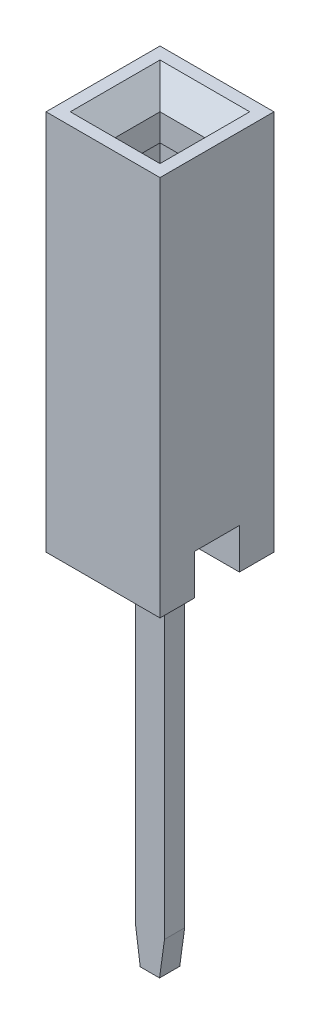
SolidWorks part; units mm, degrees
ref_plane "Vorne" through (0, 0, 0) normal (0, 0, 1) x (1, 0, 0)
ref_plane "Oben" through (0, 0, 0) normal (0, 1, 0) x (1, 0, 0)
ref_plane "Rechts" through (0, 0, 0) normal (1, 0, 0) x (0, 0, -1)
sketch "Sketch1" plane through (0, 0, 0) normal (0, 1, 0) x (1, 0, 0)
  line L1 (1.27, -1.27) -> (-1.27, -1.27)
  line L2 (1.27, -1.27) -> (1.27, 1.27)
  line L3 (1.27, 1.27) -> (-1.27, 1.27)
  line L4 (-1.27, -1.27) -> (-1.27, 1.27)
  line L5 (1.27, -1.27) -> (-1.27, 1.27) construction
  line L6 (1.27, 1.27) -> (-1.27, -1.27) construction
  point P0 (0, 0)
  dimension "D1" = 2.54
extrude "Boss-Extrude1" add sketch "Sketch1" along normal blind 8.5
shell "Shell1" thickness 0.77
chamfer "Chamfer1" distance 0.5 angle 45 4 edges at (-0.5, 8.5, 0) (0, 8.5, 0.5) (0.5, 8.5, 0) (0, 8.5, -0.5)
sketch "Sketch2" plane through (0, 0, 0) normal (1, 0, 0) x (0, 0, -1)
  line L0 (1.27, 0) -> (-1.27, 0) construction
  line L1 (0.5, 0) -> (-0.5, 0)
  line L2 (0.5, 0) -> (0.5, 0.9)
  line L3 (0.5, 0.9) -> (-0.5, 0.9)
  line L4 (-0.5, 0) -> (-0.5, 0.9)
  dimension "D1" = 1
  dimension "D2" = 0.9
extrude "Cut-Extrude1" cut sketch "Sketch2" against normal through all both and the other way through all
sketch "Sketch3" plane through (0, 0, 0) normal (0, 1, 0) x (1, 0, 0)
  line L1 (1, 1) -> (-1, 1)
  line L2 (1, 1) -> (1, -1)
  line L3 (1, -1) -> (-1, -1)
  line L4 (-1, 1) -> (-1, -1)
  line L5 (1, 1) -> (-1, -1) construction
  line L6 (1, -1) -> (-1, 1) construction
  point P0 (0, 0)
  dimension "D1" = 2
extrude "Cut-Extrude3" cut sketch "Sketch3" along normal blind 6 from offset 1.4
sketch "Sketch4" plane through (0, 0, 0) normal (0, 0, 1) x (1, 0, 0)
  line L0 (-1, 7.3) -> (-1, 1.4)
  line L1 (0, 8.5) -> (0, 0) construction
  line L2 (-0.325, -7.2) -> (-0.215, -8)
  line L3 (-0.6, 4.9) -> (-0.6, 2.8)
  line L4 (-0.325, 1.4) -> (-0.325, -7.2)
  line L5 (-0.5, 1.4) -> (0.5, 1.4) construction
  line L6 (-0.325, 1.4) -> (-1, 1.4)
  line L7 (-0.215, -8) -> (0.215, -8)
  line L8 (-1.27, 0) -> (1.27, 0) construction
  line L9 (-0.8375, 7.3296) -> (-0.6, 6.7)
  line L10 (0.8375, 7.3296) -> (0.6, 6.7)
  line L11 (0.325, 1.4) -> (1, 1.4)
  line L12 (0.325, 1.4) -> (0.325, -7.2)
  line L13 (0.6, 4.9) -> (0.6, 2.8)
  line L14 (0.325, -7.2) -> (0.215, -8)
  line L15 (1, 7.3) -> (1, 1.4)
  arc A0 (-0.6, 2.8) -> (0.6, 2.8) centre (0, 2.8) ccw
  arc A1 (-0.6, 4.9) -> (-0.6, 6.7) centre (-2.9859, 5.8) ccw
  arc A2 (-1, 7.3) -> (-0.8375, 7.3296) centre (-0.9161, 7.3) cw
  arc A3 (1, 7.3) -> (0.8375, 7.3296) centre (0.9161, 7.3) ccw
  arc A4 (0.6, 4.9) -> (0.6, 6.7) centre (2.9859, 5.8) cw
  point P29 (0, -8)
  dimension "D10" = 2.55
  dimension "D1" = 1
  dimension "D2" = 0.6
  dimension "D3" = 0.325
  dimension "D4" = 1.4
  dimension "D5" = 0.215
  dimension "D6" = 0.8
  dimension "D7" = 8
  dimension "D8" = 3.5
  dimension "D9" = 1.8
  dimension "D11" = 5.9
extrude "Boss-Extrude2" add sketch "Sketch4" along normal mid plane 0.45
